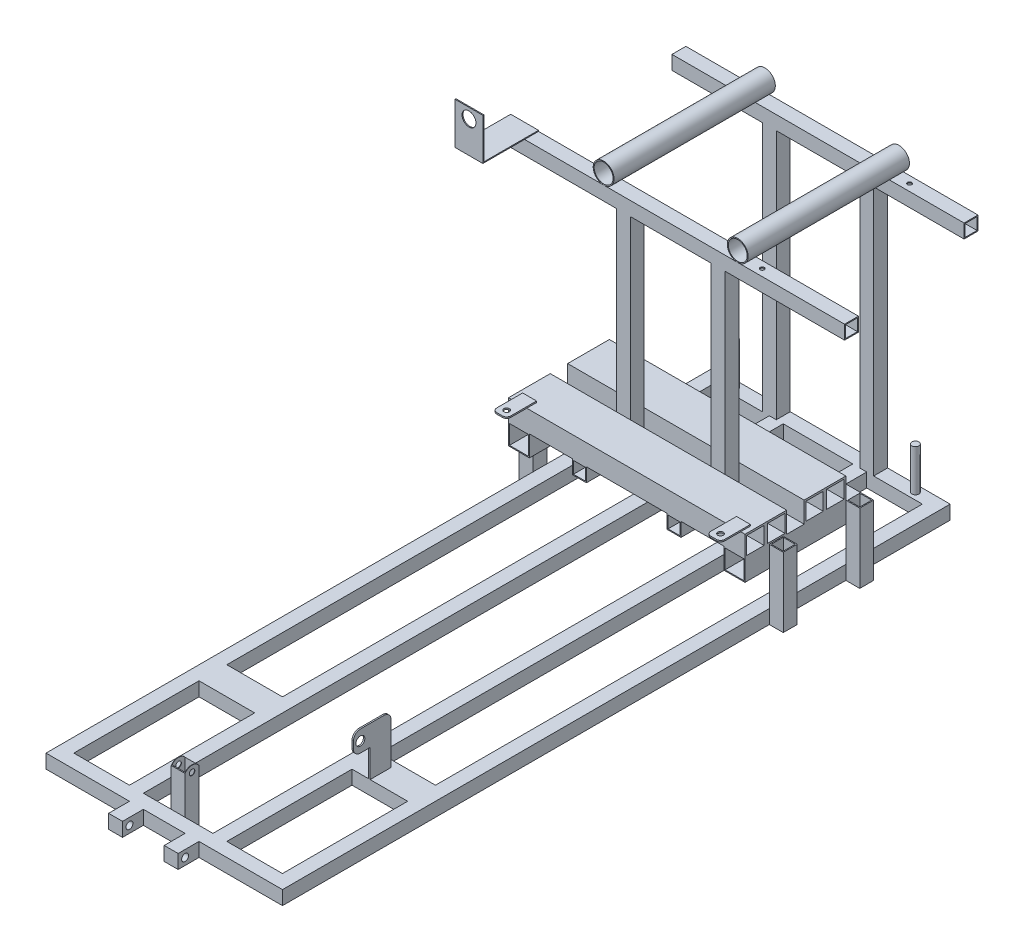
SolidWorks part; units mm, degrees
ref_plane "Front Plane" through (0, 0, 0) normal (0, 0, 1) x (1, 0, 0)
ref_plane "Top Plane" through (0, 0, 0) normal (0, 1, 0) x (1, 0, 0)
ref_plane "Right Plane" through (0, 0, 0) normal (1, 0, 0) x (0, 0, -1)
sketch "Sketch1" plane through (0, 0, 0) normal (0, 1, 0) x (1, 0, 0)
  line L0 (-75, 230) -> (75, 230)
  line L1 (-85, -240) -> (85, -240)
  line L2 (-85, -240) -> (-85, 240)
  line L3 (-85, 240) -> (85, 240)
  line L4 (85, -240) -> (85, 240)
  line L5 (-85, -240) -> (85, 240) construction
  line L6 (-85, 240) -> (85, -240) construction
  line L7 (75, -230) -> (75, 230)
  line L8 (-75, -230) -> (75, -230)
  line L9 (-75, -230) -> (-75, 230)
  line L10 (0, 240) -> (0, -240) construction
  line L11 (25, 230) -> (25, -230)
  line L12 (35, 230) -> (35, -230)
  line L13 (-35, 230) -> (-35, -230)
  line L14 (-25, 230) -> (-25, -230)
  line L15 (35, -140) -> (35, -120)
  line L16 (-75, -140) -> (-35, -140)
  line L17 (-75, -140) -> (-75, -120)
  line L18 (-75, -120) -> (-35, -120)
  line L19 (-35, -140) -> (-35, -120)
  line L20 (75, -120) -> (35, -120)
  line L21 (75, -140) -> (75, -120)
  line L22 (75, -140) -> (35, -140)
  line L23 (-25, -240) -> (-25, -255)
  line L24 (15, -240) -> (25, -240)
  line L25 (15, -240) -> (15, -255)
  line L26 (15, -255) -> (25, -255)
  line L27 (25, -240) -> (25, -255)
  line L28 (-15, -255) -> (-25, -255)
  line L29 (-15, -240) -> (-15, -255)
  line L30 (-15, -240) -> (-25, -240)
  point P0 (0, 0)
  dimension "D1" = 170
  dimension "D2" = 480
  dimension "D4" = 60
  dimension "D6" = 100
  dimension "D7" = 20
  dimension "D8" = 25
  dimension "D9" = 10
  dimension "D10" = 15
  dimension "D3" = 10
  dimension "D5" = 10
extrude "Boss-Extrude1" add sketch "Sketch1" along normal blind 10 contours L1 L4 L3 L2 L8 L9 L0 L7 | L14 L0 L13 L8 | L12 L0 L11 L8 | L22 L7 L20 L12 | L18 L9 L16 L13 | L29 L1 L23 L28 | L27 L1 L25 L26
sketch "Sketch2" plane through (25, 0, 0) normal (1, 0, 0) x (0, 0, -1)
  line L0 (-240, 10) -> (-240, 0) construction
  circle A0 centre (-250, 5) radius 2.5
  dimension "D1" = 5
  dimension "D2" = 10
extrude "Cut-Extrude1" cut sketch "Sketch2" against normal blind 57
sketch "Sketch3" plane through (0, 10, 0) normal (0, 1, 0) x (1, 0, 0)
  line L0 (85, -240) -> (85, 240) construction
  line L1 (-85, 240) -> (85, 240) construction
  line L2 (0, 240) -> (0, -267.6548) construction
  circle A0 centre (65, 235) radius 2.5
  circle A1 centre (-65, 235) radius 2.5
  dimension "D1" = 20
  dimension "D2" = 5
extrude "Boss-Extrude2" add sketch "Sketch3" along normal blind 30
sketch "Sketch4" plane through (0, 10, 0) normal (0, 1, 0) x (1, 0, 0)
  line L0 (-25, 230) -> (25, 230) construction
  line L1 (40, 230) -> (30, 230)
  line L2 (40, 230) -> (40, 240)
  line L3 (40, 240) -> (30, 240)
  line L4 (30, 230) -> (30, 240)
  line L5 (-85, 240) -> (85, 240) construction
  line L6 (85, -240) -> (85, 240) construction
  line L7 (0, 240) -> (0, 215.2561) construction
  line L8 (-30, 230) -> (-30, 240)
  line L9 (-40, 240) -> (-30, 240)
  line L10 (-40, 230) -> (-40, 240)
  line L11 (-40, 230) -> (-30, 230)
  dimension "D1" = 45
  dimension "D2" = 10
extrude "Boss-Extrude3" add sketch "Sketch4" along normal blind 180
sketch "Sketch5" plane through (0, 0, 0) normal (1, 0, 0) x (0, 0, -1)
  line L0 (230.7, 199.3) -> (239.3, 199.3)
  line L1 (230, 190) -> (240, 190)
  line L2 (230, 190) -> (230, 200)
  line L3 (230, 200) -> (240, 200)
  line L4 (240, 190) -> (240, 200)
  line L5 (239.3, 190.7) -> (239.3, 199.3)
  line L6 (230.7, 190.7) -> (239.3, 190.7)
  line L7 (230.7, 190.7) -> (230.7, 199.3)
  dimension "D1" = 10
  dimension "D2" = 10
  dimension "D3" = 0.7
extrude "Boss-Extrude5" add sketch "Sketch5" along normal mid plane 210
sketch "Sketch6" plane through (0, 10, 0) normal (0, 1, 0) x (1, 0, 0)
  line L0 (-85, -240) -> (-85, 240) construction
  line L1 (-85, 175) -> (-95, 175)
  line L2 (-85, 175) -> (-85, 165)
  line L3 (-85, 165) -> (-95, 165)
  line L4 (-95, 175) -> (-95, 165)
  line L5 (-85.7, 174.3) -> (-94.3, 174.3)
  line L6 (-85, 120) -> (-95, 120)
  line L7 (-85, 120) -> (-85, 110)
  line L8 (-85, 110) -> (-95, 110)
  line L9 (-95, 120) -> (-95, 110)
  line L10 (-94.3, 174.3) -> (-94.3, 165.7)
  line L11 (-85.7, 165.7) -> (-94.3, 165.7)
  line L12 (-85.7, 174.3) -> (-85.7, 165.7)
  line L13 (-85.7, 119.3) -> (-94.3, 119.3)
  line L14 (-94.3, 119.3) -> (-94.3, 110.7)
  line L15 (-85.7, 110.7) -> (-94.3, 110.7)
  line L16 (-85.7, 119.3) -> (-85.7, 110.7)
  line L17 (105, 240) -> (-105, 240) construction
  dimension "D1" = 10
  dimension "D2" = 10
  dimension "D3" = 10
  dimension "D6" = 75
  dimension "D7" = 130
  dimension "D4" = 0.7
  dimension "D5" = 0.7
extrude "Boss-Extrude6" add sketch "Sketch6" along normal blind 40 and the other way blind 10 separate body
sketch "Sketch7" plane through (0, 0, -175) normal (0, 0, -1) x (-1, 0, 0)
  line L0 (84.3, 49.3) -> (70.7, 49.3)
  line L1 (85, 50) -> (70, 50)
  line L2 (85, 50) -> (85, 35)
  line L3 (85, 35) -> (70, 35)
  line L4 (70, 50) -> (70, 35)
  line L5 (70.7, 49.3) -> (70.7, 35.7)
  line L6 (84.3, 35.7) -> (70.7, 35.7)
  line L7 (84.3, 49.3) -> (84.3, 35.7)
  dimension "D1" = 15
  dimension "D2" = 15
  dimension "D3" = 0.7
extrude "Boss-Extrude7" add sketch "Sketch7" against normal blind 82.5
mirror "Mirror1" about plane through (0, 0, 0) normal (1, 0, 0) of bodies 109
sketch "Sketch8" plane through (-85, 0, 0) normal (-1, 0, 0) x (0, 0, 1)
  line L0 (-136.25, 63.6566) -> (-148.75, 51.1566) construction
  line L1 (-165, 50) -> (-135, 50)
  line L2 (-165, 50) -> (-165, 65)
  line L3 (-165, 65) -> (-135, 65)
  line L4 (-150, 50) -> (-150, 65)
  line L5 (-163.75, 51.1566) -> (-151.25, 51.1566)
  line L6 (-163.75, 51.1566) -> (-163.75, 63.6566)
  line L7 (-163.75, 63.6566) -> (-151.25, 63.6566)
  line L8 (-151.25, 51.1566) -> (-151.25, 63.6566)
  line L9 (-163.75, 51.1566) -> (-151.25, 63.6566) construction
  line L10 (-163.75, 63.6566) -> (-151.25, 51.1566) construction
  line L11 (-136.25, 51.1566) -> (-148.75, 63.6566) construction
  line L12 (-148.75, 51.1566) -> (-148.75, 63.6566)
  line L13 (-136.25, 63.6566) -> (-148.75, 63.6566)
  line L14 (-136.25, 51.1566) -> (-136.25, 63.6566)
  line L15 (-136.25, 51.1566) -> (-148.75, 51.1566)
  line L16 (-135, 50) -> (-135, 65)
  line L17 (-128.75, 50) -> (-128.75, 67.8453) construction
  line L18 (-120, 50) -> (-165, 50) construction
  line L19 (-121.25, 51.1566) -> (-108.75, 63.6566) construction
  line L20 (-93.75, 63.6566) -> (-106.25, 51.1566) construction
  line L21 (-93.75, 51.1566) -> (-106.25, 63.6566) construction
  line L22 (-121.25, 63.6566) -> (-108.75, 51.1566) construction
  line L23 (-122.5, 50) -> (-122.5, 65)
  line L24 (-121.25, 51.1566) -> (-108.75, 51.1566)
  line L25 (-121.25, 51.1566) -> (-121.25, 63.6566)
  line L26 (-121.25, 63.6566) -> (-108.75, 63.6566)
  line L27 (-108.75, 51.1566) -> (-108.75, 63.6566)
  line L28 (-106.25, 51.1566) -> (-106.25, 63.6566)
  line L29 (-93.75, 63.6566) -> (-106.25, 63.6566)
  line L30 (-93.75, 51.1566) -> (-93.75, 63.6566)
  line L31 (-93.75, 51.1566) -> (-106.25, 51.1566)
  line L32 (-107.5, 50) -> (-107.5, 65)
  line L33 (-92.5, 65) -> (-122.5, 65)
  line L34 (-92.5, 50) -> (-92.5, 65)
  line L35 (-92.5, 50) -> (-122.5, 50)
  point P5 (-157.5, 57.4066)
  point P16 (-142.5, 57.4066)
  point P35 (-115, 57.4066)
  point P36 (-100, 57.4066)
  line M3 (-120, 50) -> (-165, 50)
  dimension "D1" = 15
  dimension "D2" = 15
  dimension "D3" = 12.5
  dimension "D4" = 12.5
  dimension "D5" = 7.5
  dimension "D6" = 6.25
extrude "Boss-Extrude8" add sketch "Sketch8" against normal up to vertex contours L1 L4 L3 L2 L8 L5 L6 L7 | L16 L3 L4 L14 L15 L12 L13 M3 | L35 L32 L33 L23 L27 L24 L25 L26 M3 | L35 L34 L33 L32 L30 L31 L28 L29
sketch "Sketch10" plane through (0, 50, 0) normal (0, -1, 0) x (-1, 0, 0)
  line L0 (0, 92.5) -> (0, 165) construction
  line L1 (-70, 92.5) -> (70, 92.5) construction
  line L2 (-70, 165) -> (70, 165) construction
  line L3 (70, 129.066) -> (-70, 129.066) construction
  line L4 (70, 92.5) -> (70, 175) construction
  line L5 (-70, 92.5) -> (-70, 175) construction
  line L6 (-39, 124.066) -> (-29, 134.066) construction
  line L7 (39, 134.066) -> (29, 134.066)
  line L8 (39, 134.066) -> (39, 124.066)
  line L9 (39, 124.066) -> (29, 124.066)
  line L10 (29, 134.066) -> (29, 124.066)
  line L11 (39, 134.066) -> (29, 124.066) construction
  line L12 (39, 124.066) -> (29, 134.066) construction
  line L13 (-39, 134.066) -> (-29, 124.066) construction
  line L14 (-29, 134.066) -> (-29, 124.066)
  line L15 (-39, 124.066) -> (-29, 124.066)
  line L16 (-39, 134.066) -> (-39, 124.066)
  line L17 (-39, 134.066) -> (-29, 134.066)
  line L18 (38.3, 124.766) -> (29.7, 124.766)
  line L19 (29.7, 133.366) -> (29.7, 124.766)
  line L20 (38.3, 133.366) -> (29.7, 133.366)
  line L21 (38.3, 133.366) -> (38.3, 124.766)
  line L22 (-38.3, 124.766) -> (-29.7, 124.766)
  line L23 (-29.7, 133.366) -> (-29.7, 124.766)
  line L24 (-38.3, 133.366) -> (-29.7, 133.366)
  line L25 (-38.3, 133.366) -> (-38.3, 124.766)
  point P12 (34, 129.066)
  point P21 (-34, 129.066)
  dimension "D1" = 39
  dimension "D4" = 10
  dimension "D5" = 10
  dimension "D2" = 0.7
  dimension "D3" = 0.7
extrude "Boss-Extrude9" add sketch "Sketch10" against normal up to vertex (140 mm away) separate body
sketch "Sketch12" plane through (0, 0, 0) normal (1, 0, 0) x (0, 0, -1)
  line L0 (124.766, 199.3) -> (133.366, 199.3)
  line L1 (124.066, 190) -> (134.066, 190)
  line L2 (124.066, 190) -> (124.066, 200)
  line L3 (124.066, 200) -> (134.066, 200)
  line L4 (134.066, 190) -> (134.066, 200)
  line L5 (133.366, 190.7) -> (133.366, 199.3)
  line L6 (124.766, 190.7) -> (133.366, 190.7)
  line L7 (124.766, 190.7) -> (124.766, 199.3)
  dimension "D1" = 10
  dimension "D3" = 10
  dimension "D2" = 0.7
extrude "Boss-Extrude10" add sketch "Sketch12" along normal mid plane 250 contours L4 L3 L2 L1
sketch "Sketch13" plane through (0, 0, -165) normal (0, 0, -1) x (-1, 0, 0)
  line L0 (-29.7, 49.3) -> (-38.3, 49.3)
  line L1 (-29, 50) -> (-39, 50)
  line L2 (-29, 50) -> (-29, 40)
  line L3 (-29, 40) -> (-39, 40)
  line L4 (-39, 50) -> (-39, 40)
  line L5 (-38.3, 49.3) -> (-38.3, 40.7)
  line L6 (-29.7, 40.7) -> (-38.3, 40.7)
  line L7 (-29.7, 49.3) -> (-29.7, 40.7)
  line L8 (0, 65) -> (0, 33.7719) construction
  line L9 (-85, 65) -> (85, 65) construction
  line L10 (29.7, 49.3) -> (29.7, 40.7)
  line L11 (29.7, 40.7) -> (38.3, 40.7)
  line L12 (38.3, 49.3) -> (38.3, 40.7)
  line L13 (39, 50) -> (39, 40)
  line L14 (29, 40) -> (39, 40)
  line L15 (29, 50) -> (29, 40)
  line L16 (29, 50) -> (39, 50)
  line L17 (29.7, 49.3) -> (38.3, 49.3)
  dimension "D1" = 10
  dimension "D2" = 10
  dimension "D3" = 0.7
extrude "Boss-Extrude11" add sketch "Sketch13" against normal up to vertex
sketch "Sketch14" plane through (0, 0, -240) normal (0, 0, -1) x (-1, 0, 0)
  line L0 (0, 200) -> (0, 129.7292) construction
  line L1 (-105, 200) -> (105, 200) construction
  circle A0 centre (48.1978, 207.5) radius 7.5
  circle A1 centre (48.1978, 207.5) radius 6.8
  circle A2 centre (-48.1978, 207.5) radius 6.8
  circle A3 centre (-48.1978, 207.5) radius 7.5
  dimension "D1" = 7.5
  dimension "D2" = 15
  dimension "D3" = 0.7
extrude "Boss-Extrude12" add sketch "Sketch14" against normal up to vertex (115.934 mm away) separate body
sketch "Sketch15" plane through (-125, 0, 0) normal (-1, 0, 0) x (0, 0, 1)
  line L0 (-134.066, 200) -> (-94.066, 200)
  line L1 (-94.066, 200) -> (-94.066, 230)
  line L2 (-134.066, 200.7) -> (-94.766, 200.7)
  line L3 (-94.766, 200.7) -> (-94.766, 230)
  line L4 (-134.066, 200.7) -> (-134.066, 200)
  line L5 (-94.766, 230) -> (-94.066, 230)
  dimension "D1" = 40
  dimension "D2" = 30
  dimension "D3" = 0.7
extrude "Boss-Extrude13" add sketch "Sketch15" against normal blind 20
sketch "Sketch16" plane through (0, 0, -94.066) normal (0, 0, 1) x (1, 0, 0)
  circle A0 centre (-115, 222.7306) radius 5
extrude "Cut-Extrude2" cut sketch "Sketch16" against normal blind 20
sketch "Sketch17" plane through (0, 200, 0) normal (0, 1, 0) x (1, 0, 0)
  circle A0 centre (60.831, 235) radius 1.5
  circle A1 centre (60.831, 129.066) radius 1.5
extrude "Cut-Extrude3" cut sketch "Sketch17" against normal blind 20
sketch "Sketch18" plane through (0, 10, 0) normal (0, 1, 0) x (1, 0, 0)
  line L1 (85, -240) -> (85, 240) construction
  line L2 (48, -125) -> (48, -140)
  line L3 (47, -125) -> (48, -125)
  line L4 (47, -125) -> (47, -140)
  line L5 (75, -140) -> (35, -140) construction
  line L7 (47, -140) -> (48, -140)
  dimension "D1" = 38
  dimension "D3" = 15
  dimension "D2" = 1
sketch "Sketch20" plane through (0, 65, 0) normal (0, 1, 0) x (1, 0, 0)
  line L0 (85, 92.5) -> (-85, 92.5) construction
  line L2 (81.8841, 92.5) -> (81.8841, 81)
  line L3 (78.8841, 78) -> (74.8841, 78)
  line L4 (71.8841, 93) -> (71.8841, 81)
  line L5 (71.8841, 93) -> (71.8841, 99.5274)
  line L6 (71.8841, 99.5274) -> (81.8841, 99.5274)
  line L7 (81.8841, 99.5274) -> (81.8841, 92.5)
  circle A0 centre (76.8841, 83.0631) radius 2
  arc A1 (74.8841, 78) -> (71.8841, 81) centre (74.8841, 81) cw
  arc A2 (81.8841, 81) -> (78.8841, 78) centre (78.8841, 81) cw
  point P12 (71.8841, 78)
  point P15 (81.8841, 78)
  dimension "D3" = 3
  dimension "D1" = 10
  dimension "D2" = 15
extrude "Boss-Extrude15" add sketch "Sketch20" along normal blind 1
mirror "Mirror2" about plane through (0, 0, 0) normal (1, 0, 0) of "Boss-Extrude15"
extrude "Boss-Extrude19" add sketch "Sketch18" along normal blind 35
sketch "Sketch26" plane through (0, 0, 140) normal (0, 0, 1) x (1, 0, 0)
  line L0 (48, 45) -> (48, 10) construction
  line L1 (47, 45) -> (48, 45)
  line L2 (47, 45) -> (47, 30)
  line L3 (47, 30) -> (48, 30)
  line L4 (48, 45) -> (48, 30)
  dimension "D1" = 15
extrude "Boss-Extrude20" add sketch "Sketch26" along normal blind 12
fillet "Fillet2" radius 5 3 edges at (47.5, 45, 125) (47.5, 30, 152) (47.5, 45, 152)
sketch "Sketch27" plane through (47, 0, 0) normal (-1, 0, 0) x (0, 0, 1)
  line L0 (152, 40) -> (152, 35) construction
  line L1 (130, 45) -> (147, 45) construction
  circle A0 centre (147, 37.5) radius 3.1984
  dimension "D1" = 5
  dimension "D2" = 7.5
extrude "Cut-Extrude5" cut sketch "Sketch27" against normal blind 12
sketch "Sketch28" plane through (0, 10, 0) normal (0, 1, 0) x (1, 0, 0)
  line L0 (0, -230) -> (0, -193.8599) construction
  line L1 (-25, -230) -> (25, -230) construction
  line L2 (-4.7, -220.3) -> (4.7, -220.3)
  line L3 (-5, -220) -> (5, -220)
  line L4 (-5, -220) -> (-5, -230)
  line L5 (-5, -230) -> (5, -230)
  line L6 (5, -220) -> (5, -230)
  line L7 (-5, -220) -> (5, -230) construction
  line L8 (-5, -230) -> (5, -220) construction
  line L9 (4.7, -220.3) -> (4.7, -229.7)
  line L10 (-4.7, -229.7) -> (4.7, -229.7)
  line L11 (-4.7, -220.3) -> (-4.7, -229.7)
  point P5 (0, -225)
  dimension "D1" = 10
  dimension "D2" = 10
  dimension "D3" = 0.3
extrude "Boss-Extrude21" add sketch "Sketch28" along normal blind 30 and the other way blind 10
sketch "Sketch29" plane through (5, 0, 0) normal (1, 0, 0) x (0, 0, -1)
  line L0 (-230, 40) -> (-220, 40)
  line L1 (-230, 40) -> (-230, 37.297)
  line L3 (-220, 40) -> (-220, 37.297)
  arc A0 (-220, 37.297) -> (-230, 37.297) centre (-225, 34.024) ccw
  line M1 (-220, 0) -> (-220, 40)
  line M2 (-220, 40) -> (-230, 40)
  line M3 (-230, 40) -> (-230, 10)
extrude "Cut-Extrude6" cut sketch "Sketch29" against normal blind 30 contours A0 L0 M3 | A0 M1 M2
sketch "Sketch30" plane through (5, 0, 0) normal (1, 0, 0) x (0, 0, -1)
  circle A0 centre (-225, 35.5131) radius 2
extrude "Cut-Extrude7" cut sketch "Sketch30" against normal blind 30
